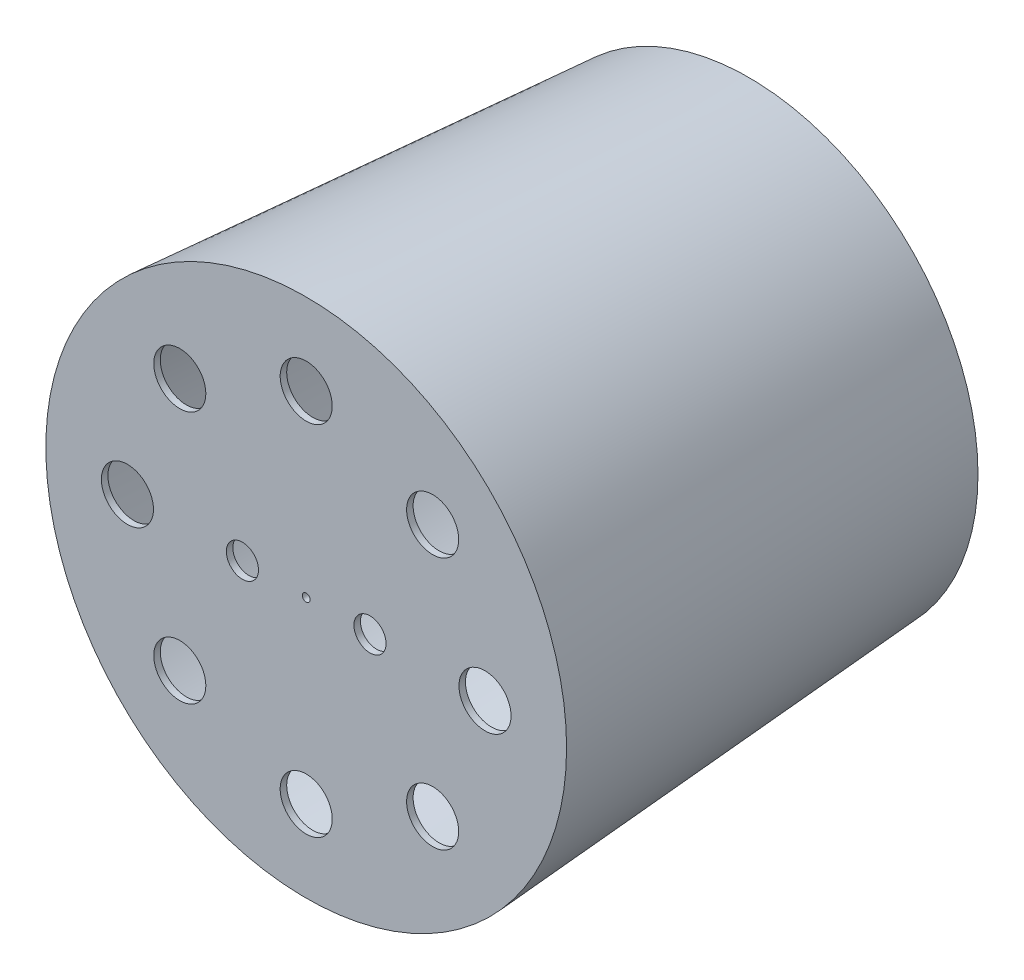
SolidWorks part; units mm, degrees
ref_plane "Alzado" through (0, 0, 0) normal (0, 0, 1) x (1, 0, 0)
ref_plane "Planta" through (0, 0, 0) normal (0, 1, 0) x (1, 0, 0)
ref_plane "Vista lateral" through (0, 0, 0) normal (1, 0, 0) x (0, 0, -1)
sketch "Croquis1" plane through (0, 0, 0) normal (0, 1, 0) x (1, 0, 0)
  line L0 (0, -85) -> (0, 85)
  line L1 (0, 85) -> (-88, 85)
  line L2 (-88, 85) -> (-100, -85)
  line L3 (-100, -85) -> (0, -85)
  point P4 (0, 0)
  dimension "D1" = 88
  dimension "D2" = 100
  dimension "D3" = 170
revolve "Revolución1" add sketch "Croquis1" angle 360 about L0
shell "Vaciado1" thickness 2.5
sketch "Croquis2" plane through (0, 0, 85) normal (0, 0, 1) x (1, 0, 0)
  line L0 (0, 0) -> (-24.5, 0) construction
  circle A0 centre (0, 0) radius 1.5
  circle A1 centre (-24.5, 0) radius 6.175
  circle A2 centre (24.5, 0) radius 6.175
  point P6 (24.5, 0)
  dimension "D1" = 3
  dimension "D4" = 12.35
  dimension "D2" = 12.35
  dimension "D5" = 24.5
extrude "Cortar-Extruir5" cut sketch "Croquis2" against normal up to next
sketch "Croquis9" plane through (0, 0, 85) normal (0, 0, 1) x (1, 0, 0)
  circle A0 centre (0, 68.6667) radius 10
  circle A1 centre (48.5547, 48.5547) radius 10
  circle A2 centre (68.6667, 0) radius 10
  circle A3 centre (48.5547, -48.5547) radius 10
  circle A4 centre (0, -68.6667) radius 10
  circle A5 centre (-48.5547, -48.5547) radius 10
  circle A6 centre (-68.6667, 0) radius 10
  circle A7 centre (-48.5547, 48.5547) radius 10
  point P18 (0, 0)
  dimension "D1" = 8
  dimension "D2" = 20
extrude "Cortar-Extruir9" cut sketch "Croquis9" against normal blind 10
